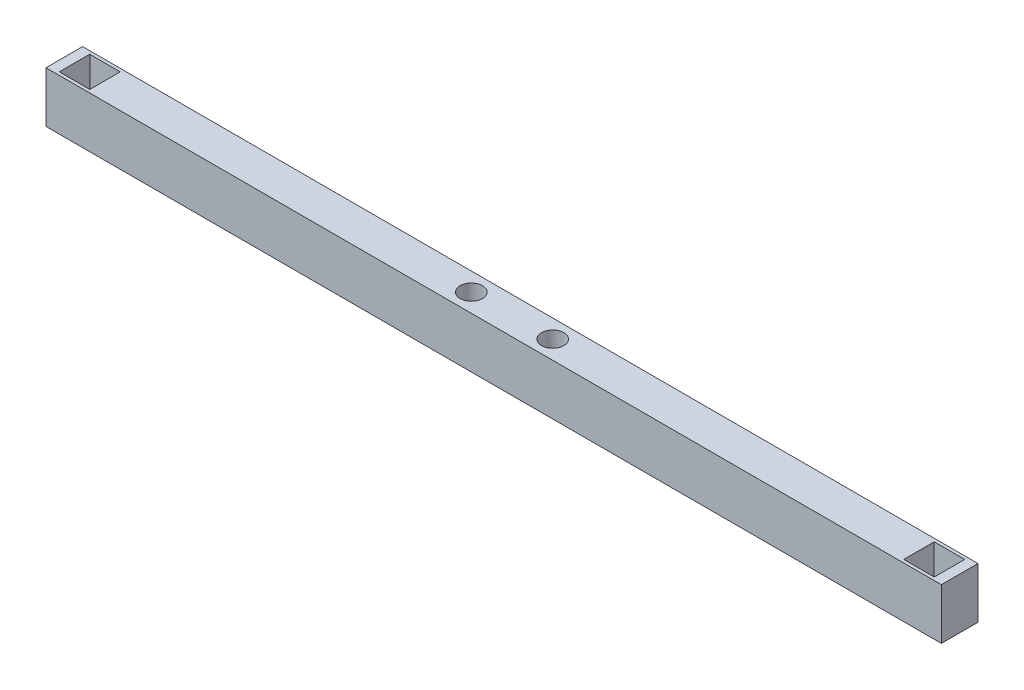
SolidWorks part; units mm, degrees
ref_plane "Front Plane" through (0, 0, 0) normal (0, 0, 1) x (1, 0, 0)
ref_plane "Top Plane" through (0, 0, 0) normal (0, 1, 0) x (1, 0, 0)
ref_plane "Right Plane" through (0, 0, 0) normal (1, 0, 0) x (0, 0, -1)
sketch "Sketch1" plane through (0, 0, 0) normal (0, 1, 0) x (1, 0, 0)
  line L1 (-440, 18) -> (440, 18)
  line L2 (-440, 18) -> (-440, -18)
  line L3 (-440, -18) -> (440, -18)
  line L4 (440, 18) -> (440, -18)
  line L5 (-440, 18) -> (440, -18) construction
  line L6 (-440, -18) -> (440, 18) construction
  point P0 (0, 0)
  dimension "D1" = 18
  dimension "D2" = 440
extrude "Boss-Extrude1" add sketch "Sketch1" along normal blind 50
sketch "Sketch2" plane through (0, 50, 0) normal (0, 1, 0) x (1, 0, 0)
  line L1 (-400, 15) -> (-430, 15)
  line L2 (-400, 15) -> (-400, -15)
  line L3 (-400, -15) -> (-430, -15)
  line L4 (-430, 15) -> (-430, -15)
  line L5 (-400, 15) -> (-430, -15) construction
  line L6 (-400, -15) -> (-430, 15) construction
  line L7 (400, 15) -> (430, 15)
  line L8 (400, 15) -> (400, -15)
  line L9 (400, -15) -> (430, -15)
  line L10 (430, 15) -> (430, -15)
  line L11 (400, 15) -> (430, -15) construction
  line L12 (400, -15) -> (430, 15) construction
  point P0 (-415, 0)
  point P5 (415, 0)
  dimension "D1" = 30
  dimension "D2" = 30
  dimension "D3" = 18
  dimension "D4" = 10
  dimension "D5" = 18
  dimension "D6" = 10
  dimension "D7" = 30
extrude "Cut-Extrude1" cut sketch "Sketch2" against normal blind 50 contours L8 L7 L10 L9 | L2 L1 L4 L3
sketch "Sketch3" plane through (0, 50, 0) normal (0, 1, 0) x (1, 0, 0)
  line L0 (-440, -18) -> (440, -18) construction
  circle A0 centre (-40, 0) radius 11
  circle A1 centre (40, 0) radius 11
  point P4 (0, 0)
  dimension "D1" = 22
  dimension "D2" = 22
  dimension "D3" = 40
  dimension "D4" = 40
  dimension "D5" = 18
  dimension "D6" = 18
extrude "Cut-Extrude2" cut sketch "Sketch3" against normal blind 50
